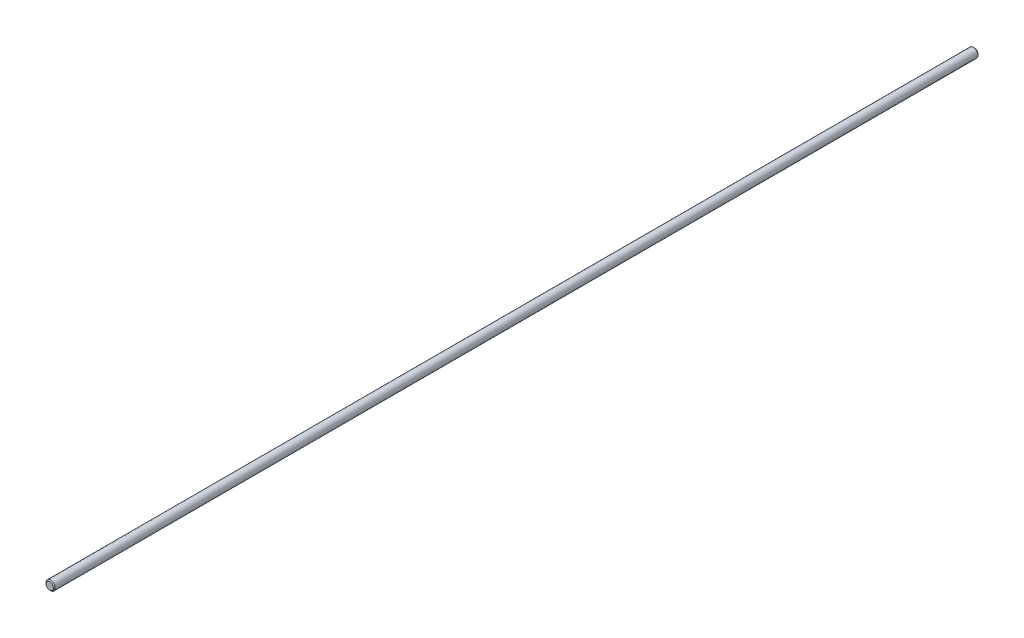
SolidWorks part; units mm, degrees
ref_plane "Front Plane" through (0, 0, 0) normal (0, 0, 1) x (1, 0, 0)
ref_plane "Top Plane" through (0, 0, 0) normal (0, 1, 0) x (1, 0, 0)
ref_plane "Right Plane" through (0, 0, 0) normal (1, 0, 0) x (0, 0, -1)
sketch "Sketch1" plane through (0, 0, 0) normal (0, 0, 1) x (1, 0, 0)
  circle A0 centre (0, 0) radius 2.495
  dimension "D1" = 4.99
extrude "Boss-Extrude1" add sketch "Sketch1" along normal blind 500
chamfer "Chamfer1" distance 0.5 angle 45 2 edges at (2.495, 0, 500) (2.495, 0, 0)
